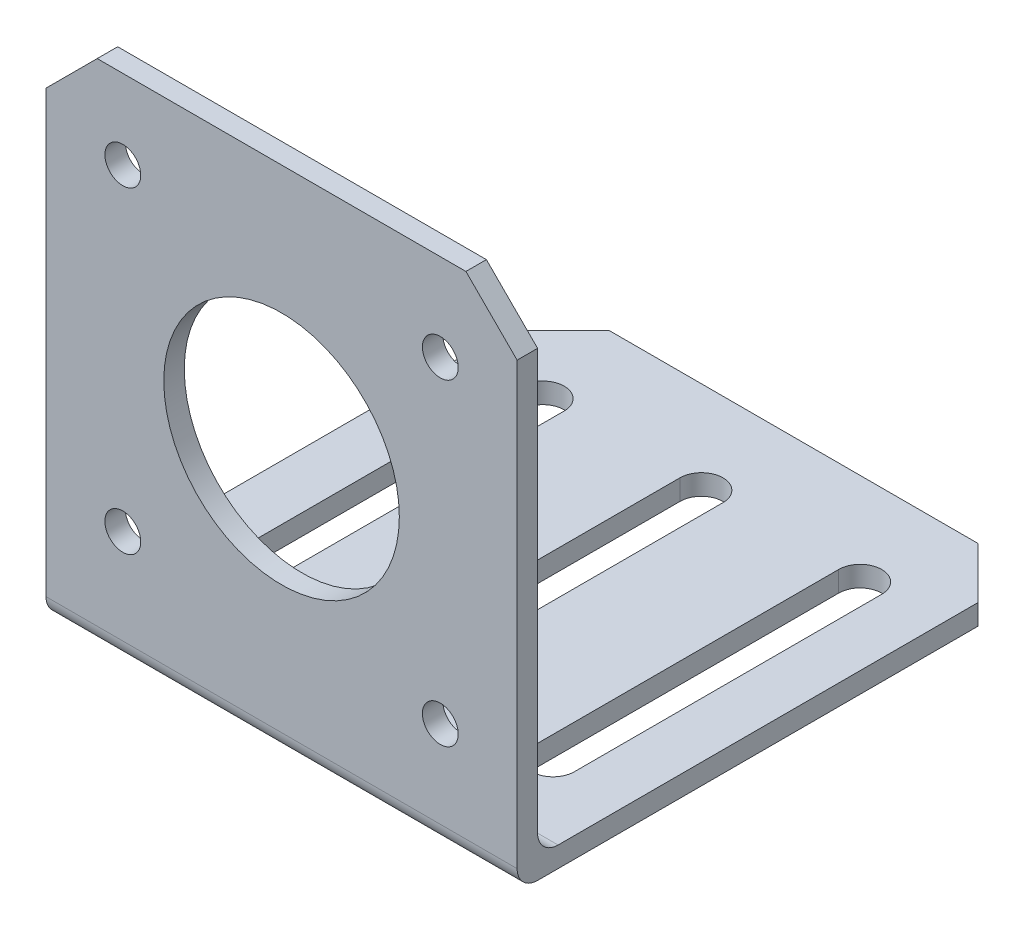
SolidWorks part; units mm, degrees
ref_plane "Alzado" through (0, 0, 0) normal (0, 0, 1) x (1, 0, 0)
ref_plane "Planta" through (0, 0, 0) normal (0, 1, 0) x (1, 0, 0)
ref_plane "Vista lateral" through (0, 0, 0) normal (1, 0, 0) x (0, 0, -1)
sketch "Croquis1" plane through (0, 0, 0) normal (1, 0, 0) x (0, 0, -1)
  line L1 (2, 0) -> (50, 0)
  line L3 (4, 2) -> (50, 2)
  line L4 (50, 0) -> (50, 2)
  line L6 (0, 2) -> (0, 50)
  line L7 (0, 50) -> (2, 50)
  line L8 (2, 4) -> (2, 50)
  arc A0 (4, 2) -> (2, 4) centre (4, 4) cw
  arc A1 (2, 0) -> (0, 2) centre (2, 2) cw
  dimension "D5" = 2
  dimension "D6" = 2
  dimension "D1" = 50
  dimension "D2" = 48
  dimension "D3" = 2
  dimension "D4" = 2
extrude "Saliente-Extruir1" add sketch "Croquis1" along normal blind 46
sketch "Croquis2" plane through (0, 0, 0) normal (0, 0, 1) x (1, 0, 0)
  line L0 (23, 50) -> (23, 0) construction
  line L1 (46, 50) -> (0, 50) construction
  line L2 (46, 0) -> (0, 0) construction
  line L3 (0, 26) -> (46, 26) construction
  line L4 (0, 50) -> (0, 2) construction
  line L5 (46, 50) -> (46, 2) construction
  line L6 (7.5, 50) -> (7.5, 0) construction
  line L7 (38.5, 50) -> (38.5, 0) construction
  line L8 (0, 41.5) -> (46, 41.5) construction
  line L9 (0, 10.5) -> (46, 10.5) construction
  circle A0 centre (23, 26) radius 11.5
  circle A1 centre (7.5, 42.25) radius 1.75
  circle A2 centre (38.5, 41.5) radius 1.75
  circle A3 centre (7.5, 11.25) radius 1.75
  circle A4 centre (38.5, 10.5) radius 1.75
  dimension "D1" = 23
  dimension "D3" = 3.5
  dimension "D2" = 31
  dimension "D4" = 31
extrude "Cortar-Extruir1" cut sketch "Croquis2" against normal through all
sketch "Croquis3" plane through (0, 0, 0) normal (0, -1, 0) x (1, 0, 0)
  line L0 (23, -2) -> (23, -50) construction
  line L1 (46, -2) -> (0, -2) construction
  line L2 (46, -50) -> (0, -50) construction
  line L3 (0, -26) -> (46, -26) construction
  line L4 (0, -2) -> (0, -50) construction
  line L5 (46, -2) -> (46, -50) construction
  line L6 (7.5, -2) -> (7.5, -50) construction
  line L7 (38.5, -2) -> (38.5, -50) construction
  line L8 (0, -11) -> (46, -11) construction
  line L9 (0, -41) -> (46, -41) construction
  line L10 (5.4, -11) -> (5.4, -41)
  line L11 (9.6, -11) -> (9.6, -41)
  line L12 (36.4, -11) -> (36.4, -41)
  line L13 (40.6, -11) -> (40.6, -41)
  arc A0 (9.6, -11) -> (5.4, -11) centre (7.5, -11) ccw
  arc A1 (40.6, -11) -> (36.4, -11) centre (38.5, -11) ccw
  arc A2 (5.4, -41) -> (9.6, -41) centre (7.5, -41) ccw
  arc A3 (36.4, -41) -> (40.6, -41) centre (38.5, -41) ccw
  dimension "D3" = 2.1
  dimension "D4" = 2.1
  dimension "D1" = 15.5
  dimension "D2" = 15
extrude "Cortar-Extruir2" cut sketch "Croquis3" against normal through all
chamfer "Chaflán1" distance 5 angle 45 4 edges at (0, 1, -50) (46, 1, -50) (46, 50, -1) (0, 50, -1)
sketch "Esboço1" plane through (0, 0, 0) normal (0, -1, 0) x (1, 0, 0)
  line L8 (9.6, -41) -> (9.6, -11) construction
  line L12 (20.9, -41) -> (20.9, -11)
  line L16 (25.1, -11) -> (25.1, -41)
  arc A2 (25.1, -41) -> (20.9, -41) centre (23, -41) cw
  arc A3 (20.9, -11) -> (25.1, -11) centre (23, -11) cw
  dimension "D1" = 11.3
  dimension "D2" = 30
  dimension "D3" = 4.2
extrude "Corte-extrusão1" cut sketch "Esboço1" against normal through all contours L16 A2 L12 A3
